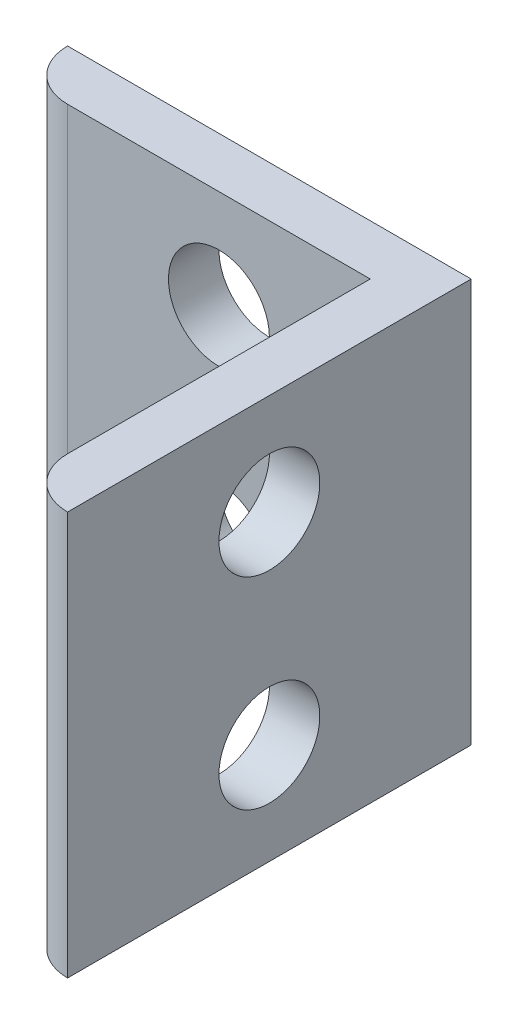
SolidWorks part; units mm, degrees
material "6061-T6 (SS)"
ref_plane "Front Plane" through (0, 0, 0) normal (0, 0, 1) x (1, 0, 0)
ref_plane "Top Plane" through (0, 0, 0) normal (0, 1, 0) x (1, 0, 0)
ref_plane "Right Plane" through (0, 0, 0) normal (1, 0, 0) x (0, 0, -1)
sketch "Sketch1" plane through (0, 0, 0) normal (0, 1, 0) x (1, 0, 0)
  line L0 (0, 0) -> (25.4, 0)
  line L1 (25.4, 0) -> (25.4, -25.4)
  line L2 (3.175, -3.175) -> (22.225, -3.175)
  line L3 (22.225, -3.175) -> (22.225, -22.225)
  line L4 (12.7, 0) -> (12.7, -3.175) construction
  line L5 (25.4, -12.7) -> (22.225, -12.7) construction
  arc A0 (0, 0) -> (3.175, -3.175) centre (3.175, 0) ccw
  arc A1 (25.4, -25.4) -> (22.225, -22.225) centre (25.4, -22.225) cw
  dimension "D1" = 3.175
  dimension "D2" = 25.4
extrude "Boss-Extrude1" add sketch "Sketch1" along normal blind 25.4
hole_wizard "1/4 (0.25) Diameter Hole1" positions "Sketch4" profile "Sketch5" hole size "1/4" standard "ANSI Inch" end condition up to next
sketch "Sketch4" plane through (22.225, 0, 0) normal (-1, 0, 0) x (0, 0, 1)
  line L0 (12.7, 25.4) -> (12.7, 0) construction
  line L1 (3.175, 25.4) -> (22.225, 25.4) construction
  line L2 (3.175, 0) -> (22.225, 0) construction
  point P8 (12.7, 19.05)
  point P10 (12.7, 6.35)
  dimension "D1" = 6.35
  dimension "D2" = 6.35
sketch "Sketch5" plane through (22.225, 19.05, 12.7) normal (0, 1, 0) x (0, 0, 1)
  line L0 (0, 0) -> (0, 3.175)
  line L1 (0, 3.175) -> (3.175, 3.175)
  line L2 (3.175, 3.175) -> (3.175, 0)
  line L5 (3.175, 0) -> (0, 0)
  line L11 (0, -6.35) -> (0, 107.95) construction
  dimension "Thru Hole Dia." = 6.35
  dimension "Thru Hole Depth" = 3.175
hole_wizard "1/4 (0.25) Diameter Hole2" positions "Sketch7" profile "Sketch8" hole size "1/4" standard "ANSI Inch" end condition up to next
sketch "Sketch7" plane through (0, 0, 3.175) normal (0, 0, 1) x (1, 0, 0)
  line L0 (12.7, 25.4) -> (12.7, 0) construction
  line L1 (3.175, 25.4) -> (22.225, 25.4) construction
  line L2 (3.175, 0) -> (22.225, 0) construction
  point P9 (12.7, 25.4)
  point P10 (12.7, 19.05)
  point P12 (12.7, 6.35)
  dimension "D1" = 6.35
  dimension "D2" = 6.35
sketch "Sketch8" plane through (12.7, 19.05, 3.175) normal (1, 0, 0) x (0, -1, 0)
  line L0 (0, 0) -> (0, 3.175)
  line L1 (0, 3.175) -> (3.175, 3.175)
  line L2 (3.175, 3.175) -> (3.175, 0)
  line L5 (3.175, 0) -> (0, 0)
  line L11 (0, -6.35) -> (0, 107.95) construction
  dimension "Thru Hole Dia." = 6.35
  dimension "Thru Hole Depth" = 3.175
